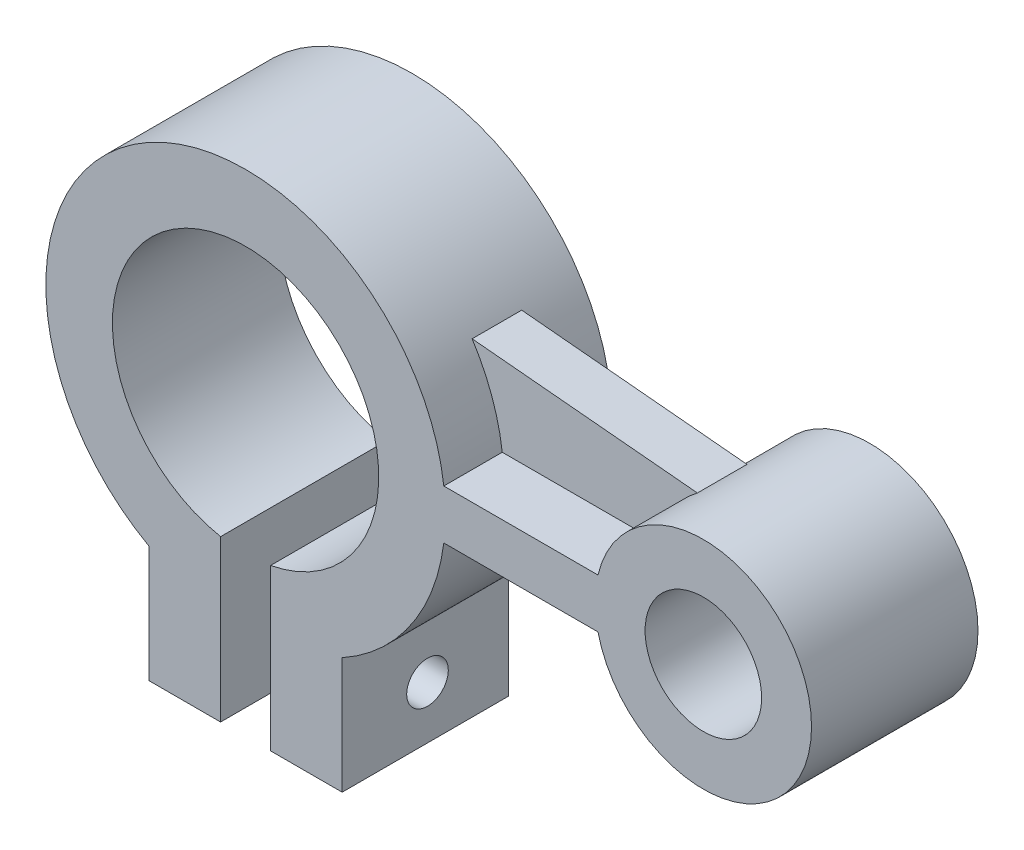
SolidWorks part; units mm, degrees
ref_plane "Front Plane" through (0, 0, 0) normal (0, 0, 1) x (1, 0, 0)
ref_plane "Top Plane" through (0, 0, 0) normal (0, 1, 0) x (1, 0, 0)
ref_plane "Right Plane" through (0, 0, 0) normal (1, 0, 0) x (0, 0, -1)
sketch "Sketch1" plane through (0, 0, 0) normal (0, 0, 1) x (1, 0, 0)
  line L0 (-49.8442, 0) -> (52.7158, 0) construction
  line L1 (-49.8442, 0) -> (-49.8442, -106.9101) construction
  line L2 (-49.8442, -40.64) -> (-42.2178, -39.918)
  line L3 (-57.4705, -88.92) -> (-79.3201, -88.92)
  line L4 (-42.2178, -39.918) -> (-42.2178, -88.92)
  line L6 (-20.3683, -53.36) -> (-20.3683, -88.92)
  line L7 (-20.3683, -88.92) -> (-42.2178, -88.92)
  line L10 (-49.8442, -40.64) -> (-57.4705, -39.918)
  line L11 (-57.4705, -39.918) -> (-57.4705, -88.92)
  line L12 (-79.3201, -53.36) -> (-79.3201, -88.92)
  line L14 (57.7043, 7.5235) -> (10.6498, 7.5235)
  line L17 (57.7043, -7.5235) -> (10.6498, -7.5235)
  circle A0 centre (-49.8442, 0) radius 40.64
  arc A1 (-20.3683, -53.36) -> (10.6498, -7.5235) centre (-49.8442, 0) ccw
  circle A2 centre (89.8558, 0) radius 17.78
  arc A3 (57.7043, -7.5235) -> (57.7043, 7.5235) centre (89.8558, 0) ccw
  arc A4 (10.6498, 7.5235) -> (-79.3201, -53.36) centre (-49.8442, 0) ccw
  dimension "D1" = 81.28
  dimension "D2" = 121.92
  dimension "D4" = 35.56
  dimension "D5" = 66.04
  dimension "D3" = 139.7
  dimension "D6" = 35.56
extrude "Boss-Extrude2" add sketch "Sketch1" along normal blind 50.8 contours L14 A4 L12 L3 L11 A0 L4 L7 L6 A1 L17 A3 A2
sketch "Sketch2" plane through (0, 7.5235, 0) normal (0, 1, 0) x (1, 0, 0)
  line L0 (10.6498, -25.4) -> (57.7043, -25.4) construction
  line L2 (10.6498, -50.8) -> (10.6498, 0) construction
  line L3 (57.7043, -50.8) -> (57.7043, 0) construction
  line L4 (57.7043, -25.4) -> (70.2103, -25.4) construction
  line L5 (9.7532, -25.4) -> (-13.8059, -25.4) construction
  line L6 (-3.6523, -32.9621) -> (-3.6523, -17.8379)
  line L7 (-3.6523, -17.8379) -> (70.2103, -17.8379)
  line L8 (70.2103, -17.8379) -> (70.2103, -32.9621)
  line L9 (-3.6523, -32.9621) -> (70.2103, -32.9621)
  point P9 (-3.6523, -25.4)
  point P14 (-3.6523, -25.4)
  point P15 (65.1843, -25.4)
  point P16 (0, 0)
  point P17 (0, 0)
  point P18 (74.9964, -25.4)
  point P19 (70.2103, -25.4)
extrude "Boss-Extrude3" add sketch "Sketch2" along normal mid plane 50.8
sketch "Sketch3" plane through (0, 0, 32.9621) normal (0, 0, 1) x (1, 0, 0)
  line L0 (70.2103, 26.5401) -> (1.4605, 32.9235)
  line L1 (1.4605, 32.9235) -> (70.2103, 32.9235)
  line L2 (70.2103, 32.9235) -> (70.2103, 26.5401)
extrude "Cut-Extrude1" cut sketch "Sketch3" against normal blind 50.8
sketch "Sketch4" plane through (-20.3683, 0, 0) normal (1, 0, 0) x (0, 0, -1)
  circle A0 centre (-24.7622, -72.8666) radius 6.35
  dimension "D1" = 12.7
extrude "Cut-Extrude2" cut sketch "Sketch4" against normal blind 63.5
